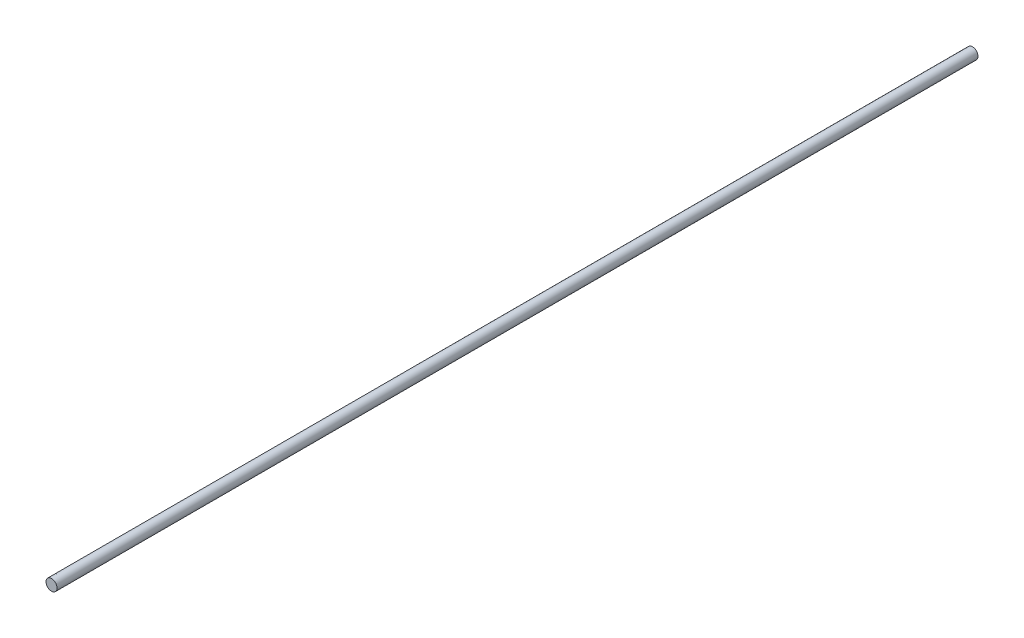
SolidWorks part; units mm, degrees
material "6061 Alloy"
ref_plane "Front Plane" through (0, 0, 0) normal (0, 0, 1) x (1, 0, 0)
ref_plane "Top Plane" through (0, 0, 0) normal (0, 1, 0) x (1, 0, 0)
ref_plane "Right Plane" through (0, 0, 0) normal (1, 0, 0) x (0, 0, -1)
sketch "Sketch1" plane through (0, 0, 0) normal (0, 0, 1) x (1, 0, 0)
  circle A0 centre (0, 0) radius 3
  dimension "D1" = 6
extrude "Boss-Extrude1" add sketch "Sketch1" along normal mid plane 500 contours A0
